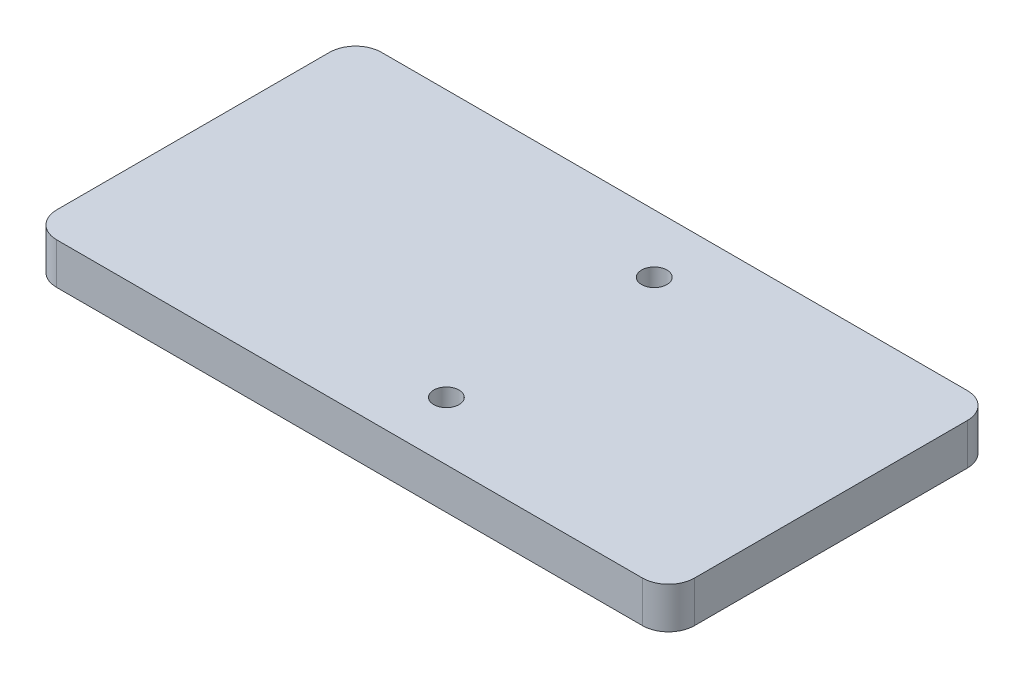
SolidWorks part; units mm, degrees
ref_plane "Front Plane" through (0, 0, 0) normal (0, 0, 1) x (1, 0, 0)
ref_plane "Top Plane" through (0, 0, 0) normal (0, 1, 0) x (1, 0, 0)
ref_plane "Right Plane" through (0, 0, 0) normal (1, 0, 0) x (0, 0, -1)
sketch "Sketch1" plane through (0, 0, 0) normal (0, 1, 0) x (1, 0, 0)
  line L0 (-49.09, 0) -> (49.09, 0) construction
  line L1 (-49.09, 25) -> (49.09, 25)
  line L2 (-49.09, 25) -> (-49.09, -25)
  line L3 (-49.09, -25) -> (49.09, -25)
  line L4 (49.09, 25) -> (49.09, -25)
  line L5 (-49.09, 25) -> (49.09, -25) construction
  line L6 (-49.09, -25) -> (49.09, 25) construction
  circle A0 centre (5.9, 16) radius 1.95
  circle A1 centre (5.9, -16) radius 1.95
  point P0 (0, 0)
  dimension "D1" = 3.9
  dimension "D2" = 16
  dimension "D3" = 16
  dimension "D4" = 50
  dimension "D5" = 98.18
  dimension "D6" = 43.19
extrude "Boss-Extrude1" add sketch "Sketch1" along normal blind 6.35
fillet "Fillet1" radius 4 4 edges at (-49.09, 3.175, 25) (-49.09, 3.175, -25) (49.09, 3.175, 25) (49.09, 3.175, -25)
